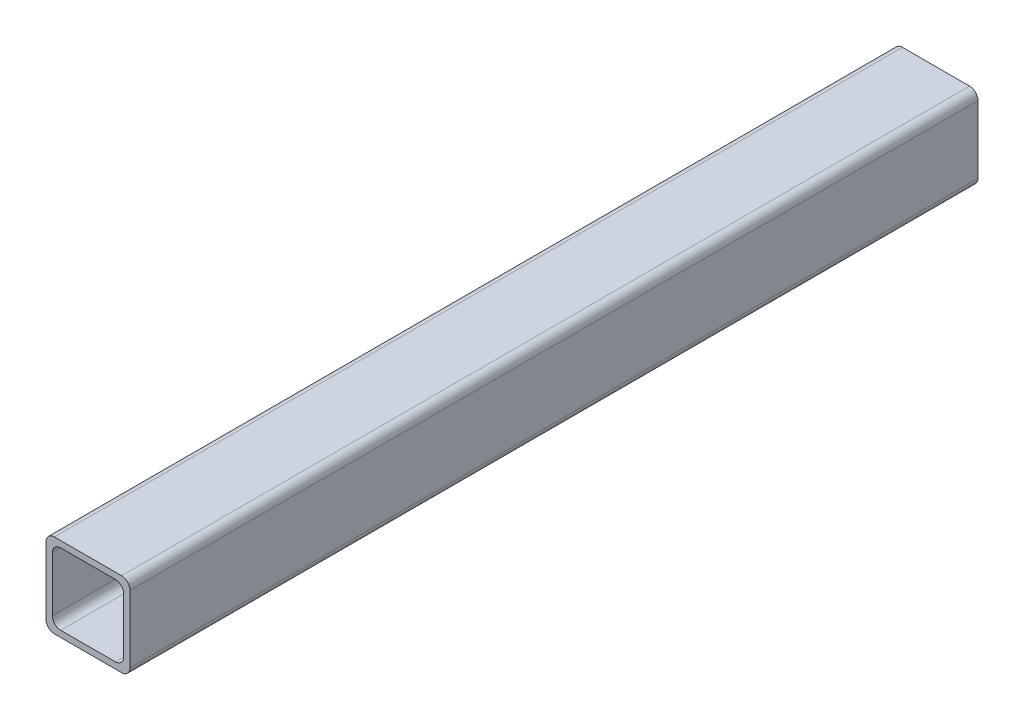
SolidWorks part; units mm, degrees
ref_plane "Front Plane" through (0, 0, 0) normal (0, 0, 1) x (1, 0, 0)
ref_plane "Top Plane" through (0, 0, 0) normal (0, 1, 0) x (1, 0, 0)
ref_plane "Right Plane" through (0, 0, 0) normal (1, 0, 0) x (0, 0, -1)
sketch "Sketch1" plane through (0, 0, 0) normal (0, 0, 1) x (1, 0, 0)
  line L0 (-8.5, 8.5) -> (8.5, 8.5)
  line L1 (-10, 10) -> (10, 10)
  line L2 (-10, 10) -> (-10, -10)
  line L3 (-10, -10) -> (10, -10)
  line L4 (10, 10) -> (10, -10)
  line L5 (-10, 10) -> (10, -10) construction
  line L6 (-10, -10) -> (10, 10) construction
  line L7 (8.5, 8.5) -> (8.5, -8.5)
  line L8 (-8.5, -8.5) -> (8.5, -8.5)
  line L9 (-8.5, 8.5) -> (-8.5, -8.5)
  point P0 (0, 0)
  dimension "D1" = 20
  dimension "D2" = 1.5
extrude "Boss-Extrude1" add sketch "Sketch1" along normal blind 202
fillet "Fillet1" radius 2 8 edges at (10, -10, 101) (8.5, -8.5, 101) (-8.5, 8.5, 101) (8.5, 8.5, 101) (-8.5, -8.5, 101) (-10, -10, 101) (10, 10, 101) (-10, 10, 101)
